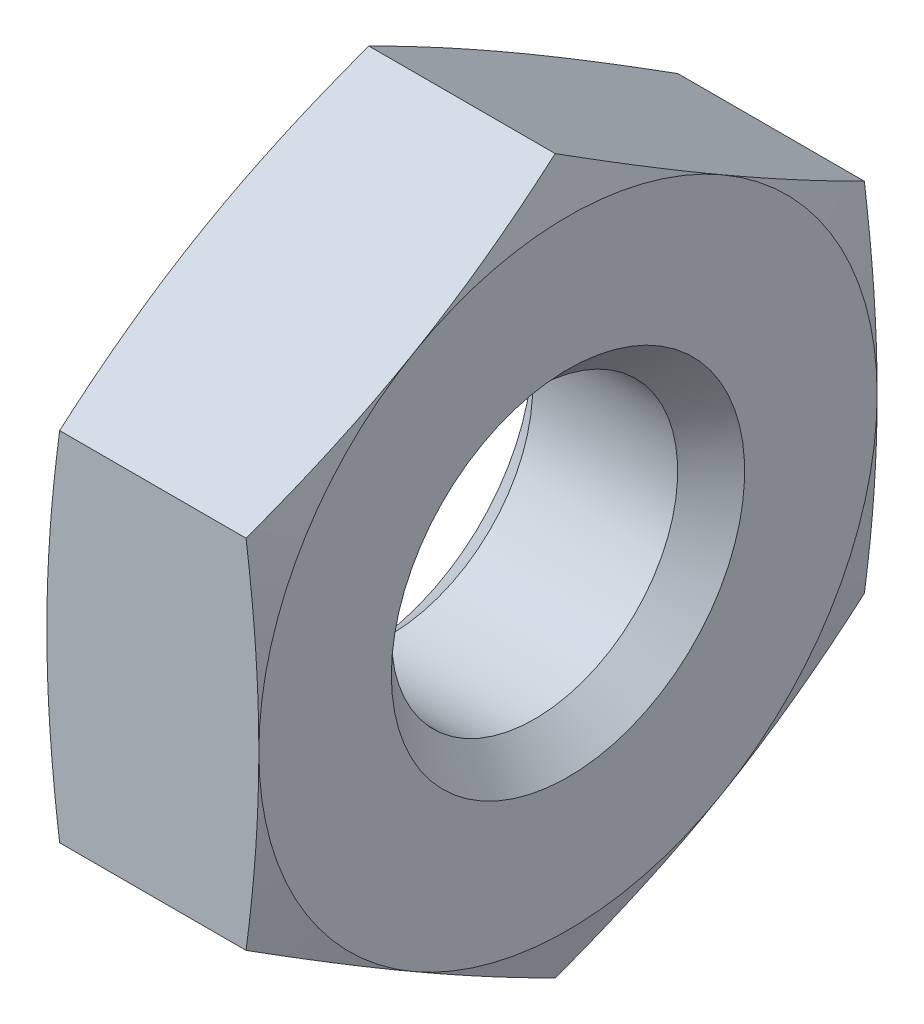
SolidWorks part; units mm, degrees
ref_plane "前视基准面" through (0, 0, 0) normal (0, 0, 1) x (1, 0, 0)
ref_plane "上视基准面" through (0, 0, 0) normal (0, 1, 0) x (1, 0, 0)
ref_plane "右视基准面" through (0, 0, 0) normal (1, 0, 0) x (0, 0, -1)
ref_plane "基准面1" through (0, 0, 0) normal (0, 0, 1) x (1, 0, 0)
sketch "草图1" plane through (0, 0, 0) normal (0, 0, 1) x (1, 0, 0)
  line L0 (0, 3.5) -> (0, 2)
  line L1 (0, 2) -> (0.379, 1.621)
  line L2 (0.379, 1.621) -> (2.021, 1.621)
  line L3 (2.021, 1.621) -> (2.4, 2)
  line L4 (2.4, 2) -> (2.4, 3.5)
  line L5 (2.4, 3.5) -> (1.8373, 5.6)
  line L6 (1.8373, 5.6) -> (0.5627, 5.6)
  line L7 (0.5627, 5.6) -> (0, 3.5)
  line L8 (2.4, 0) -> (0, 0) construction
revolve "旋转1" add sketch "草图1" angle 360 about L8
cosmetic thread "装饰螺纹线1" parameters "D1"=2.4, "D2"=4
ref_plane "基准面2" through (0, 0, 0) normal (1, 0, 0) x (0, 0, -1)
sketch "草图2" plane through (0, 0, 0) normal (1, 0, 0) x (0, 0, -1)
  line L0 (-3.5, -2.0207) -> (0, -4.0415)
  line L1 (0, -4.0415) -> (3.5, -2.0207)
  line L2 (3.5, -2.0207) -> (3.5, 2.0207)
  line L3 (3.5, 2.0207) -> (0, 4.0415)
  line L4 (0, 4.0415) -> (-3.5, 2.0207)
  line L5 (-3.5, 2.0207) -> (-3.5, -2.0207)
  circle A0 centre (0, 0) radius 20
extrude "切除-拉伸1" cut sketch "草图2" along normal blind 2.4
